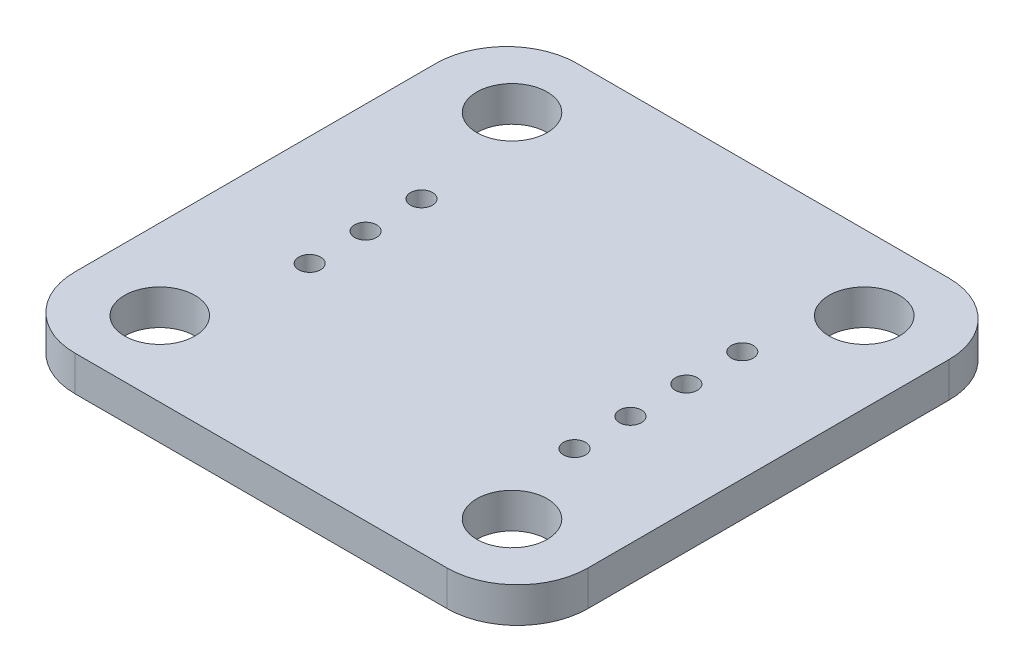
SolidWorks part; units mm, degrees
ref_plane "Спереди" through (0, 0, 0) normal (0, 0, 1) x (1, 0, 0)
ref_plane "Сверху" through (0, 0, 0) normal (0, 1, 0) x (1, 0, 0)
ref_plane "Справа" through (0, 0, 0) normal (1, 0, 0) x (0, 0, -1)
sketch "Эскиз1" plane through (0, 0, 0) normal (0, 1, 0) x (1, 0, 0)
  line L0 (-6.65, 18.7126) -> (-6.65, -15.4931) construction
  line L1 (-8.45, 11.4) -> (8.45, 11.4)
  line L2 (-11.65, 8.2) -> (-11.65, -8.2)
  line L3 (-8.45, -11.4) -> (8.45, -11.4)
  line L4 (11.65, 8.2) -> (11.65, -8.2)
  line L5 (-11.65, 11.4) -> (11.65, -11.4) construction
  line L6 (-11.65, -11.4) -> (11.65, 11.4) construction
  line L7 (-8, 8) -> (8, 8) construction
  line L8 (-8, 8) -> (-8, -8) construction
  line L9 (-8, -8) -> (7.2254, -8) construction
  line L10 (8, 8) -> (8, -8) construction
  line L11 (-8, 8) -> (8, -8) construction
  line L12 (-8, -8) -> (8, 8) construction
  line L13 (6.65, 18.7126) -> (6.65, -13.8441) construction
  line L14 (0, -1000) -> (0, 49000) construction
  line L15 (-1000, 0) -> (49000, 0) construction
  arc A0 (-11.65, -8.2) -> (-8.45, -11.4) centre (-8.45, -8.2) ccw
  arc A1 (8.45, -11.4) -> (11.65, -8.2) centre (8.45, -8.2) ccw
  arc A2 (11.65, 8.2) -> (8.45, 11.4) centre (8.45, 8.2) ccw
  arc A3 (-8.45, 11.4) -> (-11.65, 8.2) centre (-8.45, 8.2) ccw
  circle A4 centre (-8, 8) radius 1.6
  circle A5 centre (8, 8) radius 1.6
  circle A6 centre (8, -8) radius 1.6
  circle A7 centre (-8, -8) radius 1.6
  circle A8 centre (-6.65, 0) radius 0.5
  circle A9 centre (-6.65, -2.54) radius 0.5
  circle A10 centre (-6.65, 2.54) radius 0.5
  circle A11 centre (6.65, 3.81) radius 0.5
  circle A12 centre (6.65, 1.27) radius 0.5
  circle A13 centre (6.65, -1.27) radius 0.5
  circle A14 centre (6.65, -3.81) radius 0.5
  point P0 (0, 0)
  point P6 (0, 0)
  dimension "D4" = 3.2
  dimension "D5" = 3.2
  dimension "D8" = 1
  dimension "D11" = 1
  dimension "D1" = 23.3
  dimension "D2" = 22.8
  dimension "D3" = 16
  dimension "D6" = 5
  dimension "D7" = 5
  dimension "D9" = 2.54
  dimension "D10" = 2.54
  dimension "D12" = 2.54
  dimension "D13" = 2.54
  dimension "D14" = 2.54
  dimension "D15" = 1.27
extrude "Бобышка-Вытянуть1" add sketch "Эскиз1" along normal blind 1.6
